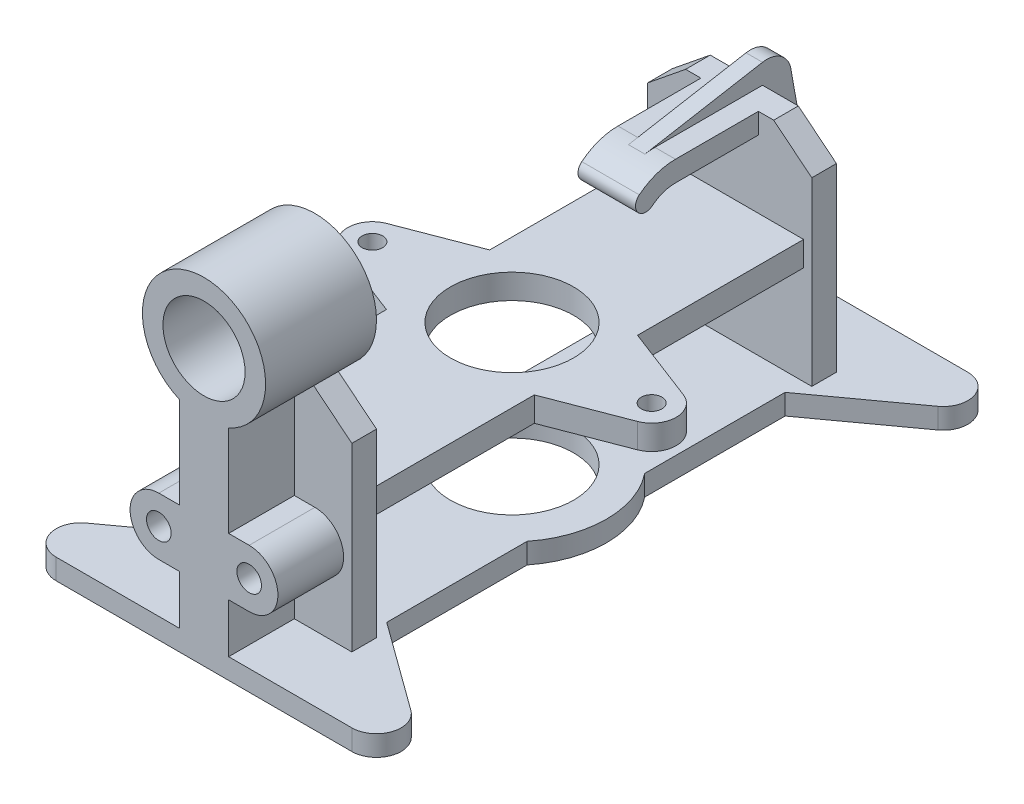
SolidWorks part; units mm, degrees
ref_plane "Front Plane" through (0, 0, 0) normal (0, 0, 1) x (1, 0, 0)
ref_plane "Top Plane" through (0, 0, 0) normal (0, 1, 0) x (1, 0, 0)
ref_plane "Right Plane" through (0, 0, 0) normal (1, 0, 0) x (0, 0, -1)
sketch "Sketch1" plane through (0, 0, 0) normal (0, 1, 0) x (1, 0, 0)
  line L0 (0, 0) -> (58.7973, 0) construction
  line L1 (0, 0) -> (0, 61.9055) construction
  line L2 (-18, 48.5058) -> (-18, 14.3178)
  line L3 (18, 48.5058) -> (18, 14.3178)
  line L4 (18, 48.5058) -> (39.5267, 64.1459)
  line L5 (-18, 48.5058) -> (-39.5267, 64.1459)
  line L6 (-36, 75) -> (36, 75)
  line L7 (-36, -75) -> (36, -75)
  line L8 (18, -48.5058) -> (39.5267, -64.1459)
  line L9 (-18, -48.5058) -> (-39.5267, -64.1459)
  line L10 (-18, -14.3178) -> (-18, -48.5058)
  line L11 (18, -14.3178) -> (18, -48.5058)
  circle A0 centre (0, 0) radius 15
  arc A1 (-18, 14.3178) -> (-18, -14.3178) centre (0, 0) ccw
  arc A2 (-36, 75) -> (-39.5267, 64.1459) centre (-36, 69) ccw
  arc A3 (39.5267, 64.1459) -> (36, 75) centre (36, 69) ccw
  arc A4 (39.5267, -64.1459) -> (36, -75) centre (36, -69) cw
  arc A5 (-36, -75) -> (-39.5267, -64.1459) centre (-36, -69) cw
  arc A6 (18, -14.3178) -> (18, 14.3178) centre (0, 0) ccw
  point P21 (0, 0)
  point P29 (0, 0)
  dimension "D1" = 30
  dimension "D2" = 46
  dimension "D3" = 12
  dimension "D4" = 138
  dimension "D5" = 72
  dimension "D6" = 36
  dimension "D7" = 36
extrude "Boss-Extrude1" add sketch "Sketch1" along normal blind 5
sketch "Sketch2" plane through (0, 0, 75) normal (0, 0, 1) x (1, 0, 0)
  line L2 (0, 67) -> (0, 0) construction
  line L3 (-36, 0) -> (36, 0) construction
  circle A0 centre (0, 67) radius 10
  circle A1 centre (0, 67) radius 15
  point P0 (4.9237, 53.2523)
  dimension "D1" = 20
  dimension "D2" = 30
  dimension "D3" = 67
extrude "Boss-Extrude2" add sketch "Sketch2" against normal blind 27
sketch "Sketch4" plane through (0, 0, 75) normal (0, 0, 1) x (1, 0, 0)
  line L0 (0, 0) -> (0, 33.9114) construction
  line L1 (-36, 0) -> (36, 0) construction
  line L2 (-6, 53.2523) -> (-6, 31)
  line L3 (6, 53.2523) -> (6, 31)
  line L4 (-36, 5) -> (36, 5) construction
  line L5 (-11, 31) -> (-6, 31)
  line L6 (-11, 17) -> (-6, 17)
  line L7 (6, 31) -> (11, 31)
  line L8 (-6, 17) -> (-6, 5)
  line L9 (6, 17) -> (6, 5)
  line L10 (6, 17) -> (11, 17)
  line L11 (-6, 5) -> (6, 5)
  arc A0 (-11, 31) -> (-11, 17) centre (-11, 24) ccw
  arc A1 (11, 31) -> (11, 17) centre (11, 24) cw
  circle A2 centre (-11, 24) radius 3
  circle A3 centre (11, 24) radius 3
  circle A4 centre (0, 67) radius 15 construction
  arc A5 (-6, 53.2523) -> (6, 53.2523) centre (0, 67) ccw
  dimension "D2" = 14
  dimension "D5" = 6
  dimension "D1" = 12
  dimension "D3" = 19
  dimension "D4" = 11
extrude "Boss-Extrude19" add sketch "Sketch4" against normal blind 16
sketch "Sketch5" plane through (0, 0, 59) normal (0, 0, -1) x (-1, 0, 0)
  line L0 (-20, 5) -> (-20, 49)
  line L1 (-20, 49) -> (-10.7237, 56.5118)
  line L2 (0, 45.1) -> (0, -45.1) construction
  line L3 (20, 49) -> (10.7237, 56.5118)
  line L4 (20, 5) -> (20, 49)
  line L5 (-36, 5) -> (36, 5) construction
  line L6 (-20, 5) -> (20, 5)
  circle A0 centre (0, 67) radius 15 construction
  arc A1 (-10.7237, 56.5118) -> (10.7237, 56.5118) centre (0, 67) ccw
  point P12 (-7.7196, 54.1389)
  dimension "D1" = 129
  dimension "D2" = 40
  dimension "D3" = 44
extrude "Boss-Extrude20" add sketch "Sketch5" along normal blind 6
pattern_linear "LPattern1" count 2 spacing 112 along (0, 0, -1) of "Boss-Extrude20"
sketch "Sketch7" plane through (0, 0, -59) normal (0, 0, -1) x (-1, 0, 0)
  line L0 (-10.7237, 56.5118) -> (10.7237, 56.5118)
  circle A0 centre (0, 67) radius 15 construction
  arc A1 (-10.7237, 56.5118) -> (10.7237, 56.5118) centre (0, 67) ccw
extrude "Boss-Extrude21" add sketch "Sketch7" against normal up to surface (6 mm away) up to face at (0, 36.0853, -53)
sketch "Sketch8" plane through (0, 5, 0) normal (0, 1, 0) x (1, 0, 0)
  line L0 (0, 0) -> (0, 36.3013) construction
  line L1 (-36.1502, 5.6015) -> (-18, 12.5687)
  line L2 (-18, 48.5058) -> (-18, 14.3178) construction
  line L3 (0, 0) -> (57.237, 0) construction
  line L4 (-36.1502, -5.6015) -> (-18, -12.5687)
  line L5 (36.1502, -5.6015) -> (18, -12.5687)
  line L6 (36.1502, 5.6015) -> (18, 12.5687)
  line L7 (-18, 53) -> (-18, 12.5687)
  line L8 (-20, 53) -> (-10.7237, 53) construction
  line L9 (-18, 53) -> (18, 53)
  line L10 (10.7237, 53) -> (20, 53) construction
  line L11 (18, 53) -> (18, 12.5687)
  line L12 (-18, -12.5687) -> (-18, -53)
  line L13 (20, -53) -> (-20, -53) construction
  line L14 (-18, -53) -> (-15, -53)
  line L16 (-15, -53) -> (-15, -48)
  line L17 (-15, -48) -> (15, -48)
  line L18 (15, -53) -> (15, -48)
  line L19 (18, -53) -> (15, -53)
  line L20 (18, -12.5687) -> (18, -53)
  arc A0 (-36.1502, 5.6015) -> (-36.1502, -5.6015) centre (-34, 0) ccw
  arc A1 (36.1502, 5.6015) -> (36.1502, -5.6015) centre (34, 0) cw
  circle A2 centre (-34, 0) radius 2.5
  circle A3 centre (34, 0) radius 2.5
  circle A4 centre (0, 0) radius 15 construction
  circle A5 centre (0, 0) radius 15
  dimension "D1" = 12
  dimension "D4" = 5
  dimension "D2" = 42
  dimension "D3" = 68
extrude "Boss-Extrude22" add sketch "Sketch8" along normal blind 6 from offset 24
sketch "Sketch9" plane through (0, 0, 0) normal (1, 0, 0) x (0, 0, -1)
  line L3 (53, 51.5118) -> (32.7996, 51.5118)
  line L5 (59, 49) -> (59, 5) construction
  line L8 (53, 56.5118) -> (53, 49) construction
  line L9 (32.7996, 56.5118) -> (53, 56.5118)
  line L10 (53, 56.5118) -> (53, 51.5118)
  arc A9 (32.7996, 51.5118) -> (27.1427, 49.5118) centre (32.7996, 42.5118) ccw
  arc A10 (27.1427, 49.5118) -> (24, 53.4007) centre (25.5713, 51.4562) cw
  arc A11 (24, 53.4007) -> (32.7996, 56.5118) centre (32.7996, 42.5118) cw
  point P10 (16.5935, 56.5118)
  point P12 (0, 0)
  point P13 (0, 0)
  dimension "D1" = 14
  dimension "D2" = 9
  dimension "D3" = 2
  dimension "D4" = 35
  dimension "D5" = 5
extrude "Boss-Extrude23" add sketch "Sketch9" along normal mid plane 14
sketch "Sketch10" plane through (0, 0, 0) normal (1, 0, 0) x (0, 0, -1)
  line L2 (75, 5) -> (64.1459, 5) construction
  line L3 (48.5058, 5) -> (64.1459, 5) construction
  line L4 (59, 49) -> (59, 5) construction
  line L5 (59, 56.5118) -> (59, 49) construction
  line L6 (59, 56.5118) -> (53, 56.5118) construction
  line L8 (75, 5) -> (64.1459, 5)
  line L9 (59, 5) -> (64.1459, 5)
  line L10 (59, 49) -> (59, 5)
  line L11 (59, 56.5118) -> (59, 49)
  line L12 (59, 56.5118) -> (53, 56.5118)
  line L14 (75, 5) -> (65.9171, 56.5118)
  line L15 (59, 61.3541) -> (30.3655, 56.2986)
  line L16 (53, 56.5118) -> (32.7996, 56.5118) construction
  line L17 (53, 56.5118) -> (32.7996, 56.5118)
  arc A5 (65.9171, 56.5118) -> (59, 61.3541) centre (60.0379, 55.4751) ccw
  arc A6 (32.7996, 56.5118) -> (24, 53.4007) centre (32.7996, 42.5118) ccw construction
  arc A8 (32.7996, 56.5118) -> (30.3655, 56.2986) centre (32.7996, 42.5118) ccw
  point P4 (20.9498, 49.8849)
  point P9 (25.6258, 54.5342)
  point P14 (0, 0)
  point P18 (62.9043, 56.5118)
  point P19 (62.4037, 56.5118)
  point P20 (0, 0)
  point P21 (-12.7439, 67.6017)
  point P22 (28.5004, 55.8354)
  point P24 (23.2983, 58.7202)
  point P25 (22.1609, 60.5427)
  point P26 (-11.0373, 65.9483)
  point P27 (23.0892, 58.0856)
  point P28 (0, 0)
  point P29 (-11.8017, 71.4632)
  point P30 (0, 0)
  point P31 (-10.2728, 64.9109)
  point P32 (65.9171, 56.5118)
  point P33 (59, 61.3319)
  point P34 (0, 0)
  dimension "D1" = 80
extrude "Boss-Extrude24" add sketch "Sketch10" along normal mid plane 4
